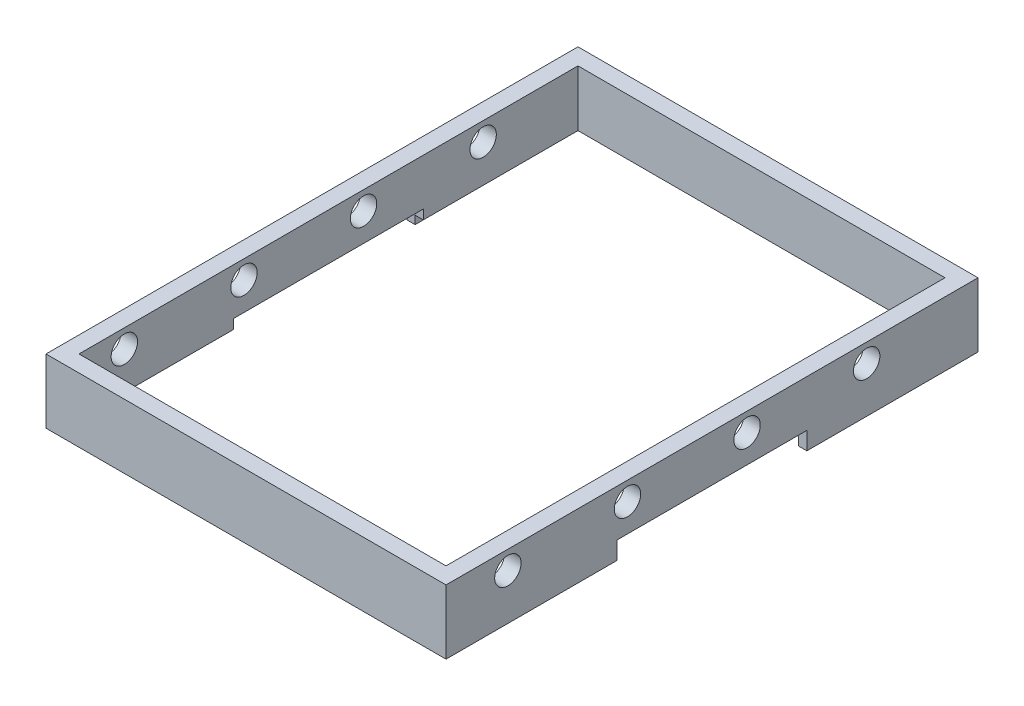
SolidWorks part; units mm, degrees
ref_plane "Front Plane" through (0, 0, 0) normal (0, 0, 1) x (1, 0, 0)
ref_plane "Top Plane" through (0, 0, 0) normal (0, 1, 0) x (1, 0, 0)
ref_plane "Right Plane" through (0, 0, 0) normal (1, 0, 0) x (0, 0, -1)
sketch "Sketch1" plane through (0, 0, 0) normal (0, 1, 0) x (1, 0, 0)
  line L1 (-44.5, -60.5) -> (44.5, -60.5)
  line L2 (-44.5, -60.5) -> (-44.5, 60.5)
  line L3 (-44.5, 60.5) -> (44.5, 60.5)
  line L4 (44.5, -60.5) -> (44.5, 60.5)
  line L5 (-44.5, -60.5) -> (44.5, 60.5) construction
  line L6 (-44.5, 60.5) -> (44.5, -60.5) construction
  line L7 (-48.5, -64.5) -> (48.5, -64.5)
  line L8 (-48.5, -64.5) -> (-48.5, 64.5)
  line L9 (-48.5, 64.5) -> (48.5, 64.5)
  line L10 (48.5, -64.5) -> (48.5, 64.5)
  line L11 (-48.5, -64.5) -> (48.5, 64.5) construction
  line L12 (-48.5, 64.5) -> (48.5, -64.5) construction
  point P0 (0, 0)
  point P6 (0, 0)
  dimension "D1" = 4
  dimension "D2" = 4
  dimension "D3" = 121
  dimension "D4" = 89
extrude "Boss-Extrude1" add sketch "Sketch1" along normal blind 11.3
sketch "Sketch3" plane through (48.5, 0, 0) normal (1, 0, 0) x (0, 0, -1)
  line L0 (-49.5, 6.8) -> (-60.5, 6.8) construction
  line L1 (-60.5, 11.3) -> (-60.5, 0) construction
  line L3 (-64.5, 11.3) -> (64.5, 11.3) construction
  circle A0 centre (-49.5, 6.8) radius 3.2
  dimension "D3" = 6.4
  dimension "D1" = 4.5
  dimension "D2" = 11
extrude "Cut-Extrude1" cut sketch "Sketch3" against normal through all
pattern_linear "LPattern1" count 4 spacing 29 along (0, 0, -1) of "Cut-Extrude1"
sketch "Sketch5" plane through (0, 0, 0) normal (0, -1, 0) x (1, 0, 0)
  line L0 (44.5, 60.5) -> (44.5, 23)
  line L1 (44.5, 60.5) -> (44.5, -60.5) construction
  line L2 (44.5, 23) -> (48.5, 23)
  line L3 (48.5, 64.5) -> (48.5, -64.5) construction
  line L4 (48.5, 23) -> (48.5, 64.5)
  line L5 (48.5, 64.5) -> (-48.5, 64.5)
  line L6 (-48.5, 64.5) -> (-48.5, 23)
  line L7 (-48.5, -64.5) -> (-48.5, 64.5) construction
  line L8 (-48.5, 23) -> (-44.5, 23)
  line L9 (-44.5, -60.5) -> (-44.5, 60.5) construction
  line L10 (-44.5, 23) -> (-44.5, 60.5)
  line L11 (-44.5, 60.5) -> (44.5, 60.5)
  dimension "D1" = 37.5
extrude "Boss-Extrude2" add sketch "Sketch5" along normal blind 2.3
sketch "Sketch6" plane through (0, -2.3, 0) normal (0, -1, 0) x (1, 0, 0)
  line L0 (-48.5, 23) -> (-48.5, 64.5)
  line L1 (-48.5, 64.5) -> (48.5, 64.5)
  line L2 (48.5, 64.5) -> (48.5, 23)
  line L3 (48.5, 23) -> (46.5, 23)
  line L5 (46.5, 23) -> (46.5, 62.5)
  line L6 (-48.5, 23) -> (-46.5, 23)
  line L7 (-48.5, 23) -> (-44.5, 23) construction
  line L8 (-46.5, 23) -> (-46.5, 62.5)
  line L9 (-46.5, 62.5) -> (46.5, 62.5)
  line L10 (-46.5, 62.5) -> (-46.5, 64.5) construction
  dimension "D1" = 2
extrude "Boss-Extrude3" add sketch "Sketch6" along normal blind 2
mirror "Mirror1" about plane through (0, 0, 0) normal (0, 0, 1) of "Boss-Extrude3", "Boss-Extrude2"
